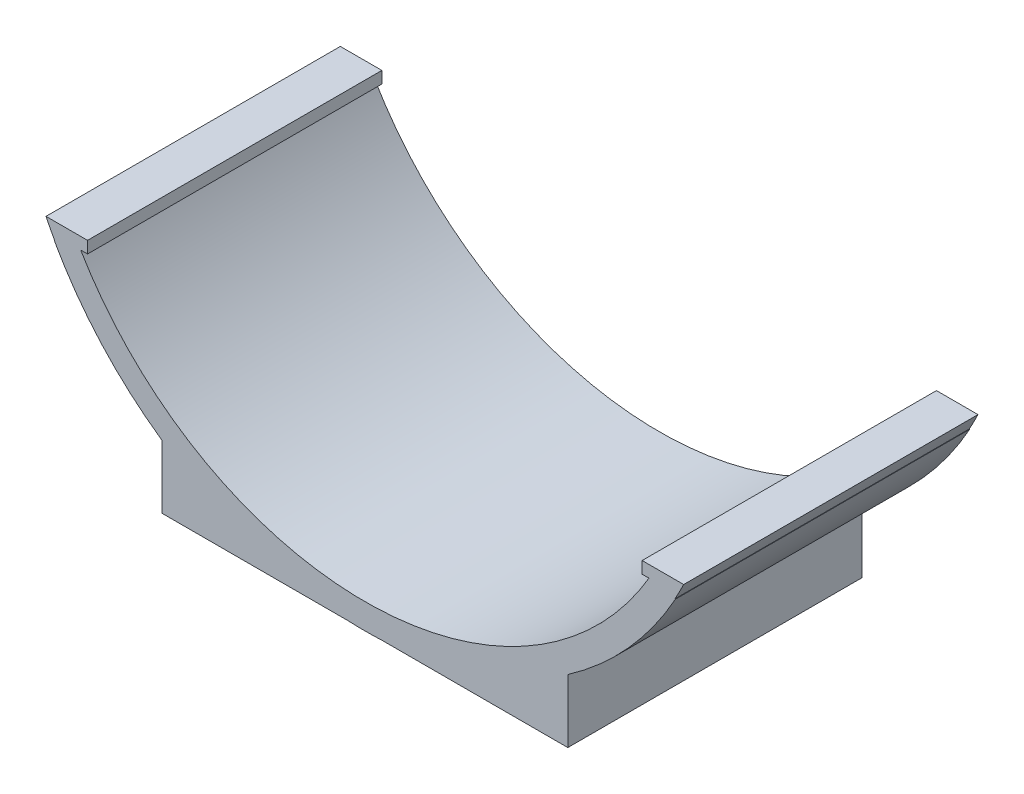
SolidWorks part; units mm, degrees
ref_plane "前视基准面" through (0, 0, 0) normal (0, 0, 1) x (1, 0, 0)
ref_plane "上视基准面" through (0, 0, 0) normal (0, 1, 0) x (1, 0, 0)
ref_plane "右视基准面" through (0, 0, 0) normal (1, 0, 0) x (0, 0, -1)
sketch "草图1" plane through (0, 0, 0) normal (0, 0, 1) x (1, 0, 0)
  arc A0 (-203, 0) -> (203, 0) centre (0, 0) ccw
  arc A1 (-210, 0) -> (210, 0) centre (0, 0) ccw
  arc A2 (-203, 0) -> (203, 0) centre (0, 0) ccw
  circle A3 centre (0, 0) radius 210
  circle A4 centre (0, 0) radius 203
  point P12 (0, 0)
extrude "凸台-拉伸2" add sketch "草图1" along normal blind 174
sketch "草图2" plane through (0, 0, 174) normal (0, 0, 1) x (1, 0, 0)
  line L0 (-173.7354, -102) -> (-170.7354, -102)
  line L1 (-170.7354, -102) -> (-170.7354, -105)
  line L2 (-170.7354, -105) -> (-173.7354, -105)
  line L3 (173.7354, -102) -> (170.7354, -102)
  line L4 (-173.7354, -102) -> (-175.5135, -102)
  line L6 (173.7354, -102) -> (175.5135, -102)
  line L7 (173.7354, -105) -> (170.7354, -105)
  line L8 (170.7354, -105) -> (170.7354, -102)
  circle A0 centre (0, 0) radius 203 construction
  arc A1 (0, -203) -> (-173.7354, -105) centre (0, 0) ccw
  circle M4 centre (0, 0) radius 203
extrude "凸台-拉伸4" add sketch "草图2" against normal up to surface (174 mm away) contours L0 L4 L2 L1 M4 | L8 L7 L6 L3 M4 up to face at (203, 0, 0)
sketch "草图3" plane through (0, 0, 174) normal (0, 0, 1) x (1, 0, 0)
  line L0 (-170.7354, -102) -> (238.3336, -102)
  line L1 (238.3336, -102) -> (254.3342, 272.2925)
  line L2 (254.3342, 272.2925) -> (-334.5694, 221.8511)
  line L3 (-170.7354, -102) -> (-306.8306, -102)
  line L4 (-306.8306, -102) -> (-334.5694, 221.8511)
extrude "切除-拉伸1" cut sketch "草图3" against normal blind 654
ref_plane "基准面1" through (0, -209.75, 0) normal (0, 1, 0) x (1, 0, 0)
sketch "草图5" plane through (0, 0, 174) normal (0, 0, 1) x (1, 0, 0)
  line L0 (0, -209.75) -> (120, -209.75)
  line L1 (95.7, -209.75) -> (-95.7, -209.75) construction
  line L2 (120, -209.75) -> (120, -172.0322)
  line L3 (0, -209.75) -> (-120, -209.75)
  line L4 (-120, -209.75) -> (-120, -172.0322)
  arc A0 (-120, -172.0322) -> (120, -172.0322) centre (0, 0) ccw
  arc M3 (-183.5647, -102) -> (183.5647, -102) centre (0, 0) ccw
extrude "凸台-拉伸5" add sketch "草图5" against normal up to surface (174 mm away) contours L4 L3 M3 | L0 L2 M3 up to face at (0, -129.25, 0)
sketch "草图6" plane through (0, 0, 174) normal (0, 0, 1) x (1, 0, 0)
  line L0 (-175.5135, -102) -> (-166.1957, -102)
  line L1 (175.5135, -102) -> (166.1957, -102)
  arc A0 (-166.1957, -102) -> (166.1957, -102) centre (0, 0) ccw
  arc A1 (-175.5135, -102) -> (175.5135, -102) centre (0, 0) ccw
extrude "凸台-拉伸6" add sketch "草图6" against normal up to surface (174 mm away) up to face at (0, -151.228, 0)
sketch "草图7" plane through (0, 0, 174) normal (0, 0, 1) x (1, 0, 0)
  line L0 (-166.9331, -92) -> (-166.9331, -95)
  line L1 (171.9331, -92) -> (166.9331, -92)
  line L2 (-171.9331, -92) -> (-166.9331, -92)
  line L3 (-188.4969, -92) -> (-171.9331, -92)
  line L4 (171.9331, -92) -> (188.4969, -92)
  line L5 (-166.9331, -95) -> (-170.2939, -95)
  line L6 (166.9331, -92) -> (166.9331, -95)
  line L7 (166.9331, -95) -> (170.2939, -95)
  arc A1 (-188.4969, -92) -> (188.4969, -92) centre (0, 0) ccw
  arc A2 (-170.2939, -95) -> (170.2939, -95) centre (0, 0) ccw
extrude "凸台-拉伸7" add sketch "草图7" against normal up to surface (174 mm away) up to face at (0, -169.2192, 0)
sketch "草图8" plane through (0, 0, 0) normal (0, 0, -1) x (-1, 0, 0)
  line L0 (166.9331, -92) -> (163.9331, -92)
  line L1 (163.9331, -92) -> (163.9331, -99)
  line L2 (163.9331, -99) -> (168, -99)
  line L3 (166.9331, -92) -> (166.9331, -95)
  line L4 (166.9331, -95) -> (170.2939, -95)
  line L6 (-166.9331, -95) -> (-170.2939, -95)
  line L7 (-166.9331, -92) -> (-166.9331, -95)
  line L8 (-163.9331, -99) -> (-168, -99)
  line L9 (-163.9331, -92) -> (-163.9331, -99)
  line L10 (-166.9331, -92) -> (-163.9331, -92)
  arc A0 (-170.2939, -95) -> (170.2939, -95) centre (0, 0) ccw construction
  arc A1 (168, -99) -> (170.2939, -95) centre (0, 0) ccw
  arc A2 (-168, -99) -> (-170.2939, -95) centre (0, 0) cw
extrude "凸台-拉伸8" add sketch "草图8" against normal up to surface (174 mm away) up to face at (0, -135.959, 174)
